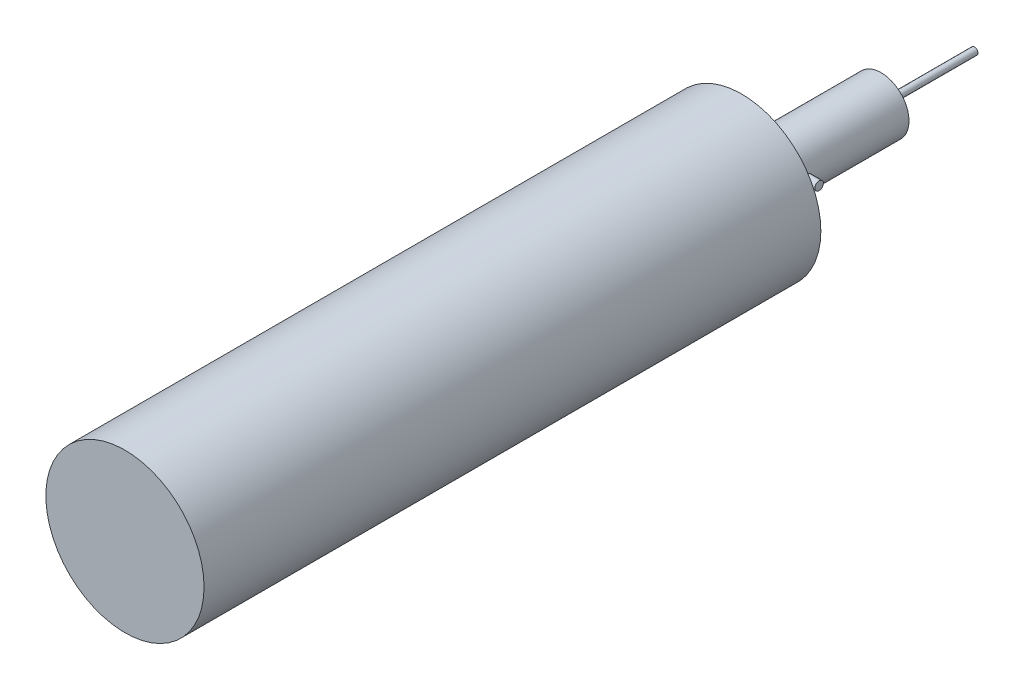
SolidWorks part; units mm, degrees
ref_plane "Plan de face" through (0, 0, 0) normal (0, 0, 1) x (1, 0, 0)
ref_plane "Plan de dessus" through (0, 0, 0) normal (0, 1, 0) x (1, 0, 0)
ref_plane "Plan de droite" through (0, 0, 0) normal (1, 0, 0) x (0, 0, -1)
sketch "Esquisse1" plane through (0, 0, 0) normal (0, 0, 1) x (1, 0, 0)
  circle A0 centre (0, 0) radius 11.35
  dimension "D1" = 22.7
extrude "Boss.-Extru.1" add sketch "Esquisse1" along normal blind 88.5
sketch "Esquisse2" plane through (0, 0, 0) normal (0, 0, -1) x (-1, 0, 0)
  circle A0 centre (0, 0) radius 4
extrude "Boss.-Extru.2" add sketch "Esquisse2" along normal blind 20
sketch "Esquisse4" plane through (0, 0, 0) normal (0, 0, -1) x (-1, 0, 0)
  line L1 (0, -4) -> (0.5907, -4)
  line L2 (0, -4) -> (0, 6.9808)
  line L3 (0, 6.9808) -> (0.5907, 6.9808)
  line L4 (0.5907, -4) -> (0.5907, 6.9808)
  circle A0 centre (0, 0) radius 4 construction
extrude "Boss.-Extru.3" add sketch "Esquisse4" along normal blind 20
sketch "Esquisse5" plane through (0, 0, 0) normal (1, 0, 0) x (0, 0, -1)
  circle A0 centre (5.5, 0) radius 0.6151
  dimension "D1" = 5.5
extrude "Boss.-Extru.4" add sketch "Esquisse5" along normal blind 5.6
sketch "Esquisse7" plane through (0, 0, -20) normal (0, 0, -1) x (-1, 0, 0)
  line L0 (0, 6.9808) -> (0, 4)
  line L3 (0, 6.9808) -> (0.5907, 6.9808)
  line L5 (0.5907, 6.9808) -> (0.5907, 3.9562)
  circle A0 centre (0, 0) radius 4
  line M5 (0.5907, 3.9562) -> (0.5907, 6.9808)
  line M6 (0.5907, 6.9808) -> (0, 6.9808)
  line M7 (0, 6.9808) -> (0, 4)
  dimension "D1" = 8
  dimension "D2" = 2.9808
  dimension "D3" = 0.5907
extrude "Enlèv. mat.-Extru.2" cut sketch "Esquisse7" against normal blind 20 contours A0 M5 M6 M7
sketch "Esquisse8" plane through (0, 0, -20) normal (0, 0, -1) x (-1, 0, 0)
  line L0 (0, -4) -> (0, -4.4873)
  line L1 (0, -4.4873) -> (0.5907, -4.4873)
  line L2 (0.5907, -4.4873) -> (0.5907, -3.9562)
  circle A1 centre (0, 0) radius 4
  line M4 (0.5907, -4) -> (0.5907, -3.9562)
  line M6 (0, -4) -> (0.5907, -4)
  dimension "D1" = 8
  dimension "D2" = 0.5312
extrude "Enlèv. mat.-Extru.3" cut sketch "Esquisse8" against normal blind 20 contours A1 M6 M4
sketch "Sketch1" plane through (0, 0, -20) normal (0, 0, -1) x (-1, 0, 0)
  circle A0 centre (0, 0) radius 0.5
  dimension "D1" = 1
extrude "Boss-Extrude1" add sketch "Sketch1" along normal blind 13.4
